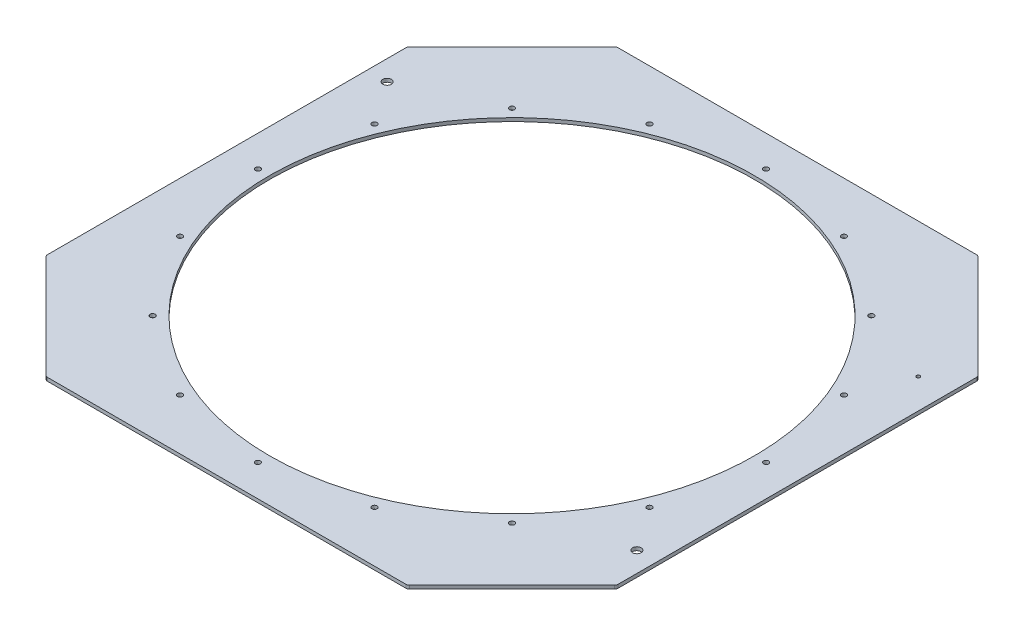
SolidWorks part; units mm, degrees
material "ASTM A36 Steel"
ref_plane "Front Plane" through (0, 0, 0) normal (0, 0, 1) x (1, 0, 0)
ref_plane "Top Plane" through (0, 0, 0) normal (0, 1, 0) x (1, 0, 0)
ref_plane "Right Plane" through (0, 0, 0) normal (1, 0, 0) x (0, 0, -1)
sketch "Sketch1" plane through (0, 0, 0) normal (0, 1, 0) x (1, 0, 0)
  line L5 (-243.4315, -243.4315) -> (243.4315, 243.4315) construction
  line L6 (-300, 300) -> (243.4315, -243.4315) construction
  line L18 (315.0665, 496.5) -> (497.5, 314.0665)
  line L19 (-314.0665, -497.5) -> (315.0665, -497.5)
  line L20 (-496.5, -315.0665) -> (-496.5, 314.0665)
  line L21 (-314.0665, 496.5) -> (315.0665, 496.5)
  line L22 (497.5, -315.0665) -> (497.5, 314.0665)
  line L23 (-405.7832, -405.7832) -> (405.7832, 405.7832) construction
  line L24 (-405.2832, 405.2832) -> (406.2832, -406.2832) construction
  line L25 (497.5, -315.0665) -> (315.0665, -497.5)
  line L30 (406.2832, -406.2832) -> (-405.2832, 405.2832) construction
  line L31 (498.06, 498.06) -> (-405.7832, -405.7832) construction
  line L32 (-496.5, -315.0665) -> (-314.0665, -497.5)
  line L33 (-314.0665, 496.5) -> (-496.5, 314.0665)
  point P0 (0, 0)
  point P7 (0, 0)
  point P10 (0, 0)
  point P17 (0, 0)
  dimension "D1" = 258
  dimension "D2" = 135
  dimension "D3" = 258
  dimension "D4" = 994
  dimension "D5" = 258
  dimension "D6" = 258
  dimension "D7" = 135
  dimension "D8" = 135
  dimension "D9" = 994
  dimension "D10" = 496.5
  dimension "D11" = 497.5
extrude "Boss-Extrude1" add sketch "Sketch1" along normal blind 6
sketch "Sketch2" plane through (0, 6, 0) normal (0, 1, 0) x (1, 0, 0)
  circle A0 centre (0, 0) radius 422.5
  dimension "D1" = 845
extrude "Cut-Extrude1" cut sketch "Sketch2" against normal blind 6
sketch "Sketch3" plane through (0, 6, 0) normal (0, 1, 0) x (1, 0, 0)
  circle A0 centre (0, 0) radius 442.5 construction
  circle A1 centre (0, 442.5) radius 4.5
  dimension "D1" = 885
  dimension "D2" = 9
extrude "Cut-Extrude2" cut sketch "Sketch3" against normal blind 6
pattern_circular "CirPattern1" count 16 every 22.5 about axis through (0, 0, 0) along (0, 1, 0) of "Cut-Extrude2"
sketch "Sketch4" plane through (0, 6, 0) normal (0, 1, 0) x (1, 0, 0)
  line L1 (497.5, -315.0665) -> (497.5, 314.0665) construction
  circle A0 centre (445.5, 262.0665) radius 3
  dimension "D3" = 6
  dimension "D1" = 52
  dimension "D2" = 52
extrude "Cut-Extrude3" cut sketch "Sketch4" against normal blind 10
sketch "Sketch5" plane through (0, 6, 0) normal (0, 1, 0) x (1, 0, 0)
  line L0 (-496.5, 314.0665) -> (-496.5, -315.0665) construction
  line L1 (497.5, -315.0665) -> (497.5, 314.0665) construction
  circle A0 centre (-461.5, 244.0665) radius 7.5
  circle A1 centre (462.5, -245.0665) radius 7.5
  dimension "D3" = 70
  dimension "D5" = 15
  dimension "D6" = 15
  dimension "D1" = 35
  dimension "D2" = 70
  dimension "D4" = 35
extrude "Cut-Extrude4" cut sketch "Sketch5" against normal blind 10
fillet "Fillet1" radius 6 8 edges at (497.5, 3, -314.0665) (315.0665, 3, -496.5) (-314.0665, 3, -496.5) (-496.5, 3, -314.0665) (-496.5, 3, 315.0665) (-314.0665, 3, 497.5) (315.0665, 3, 497.5) (497.5, 3, 315.0665)
